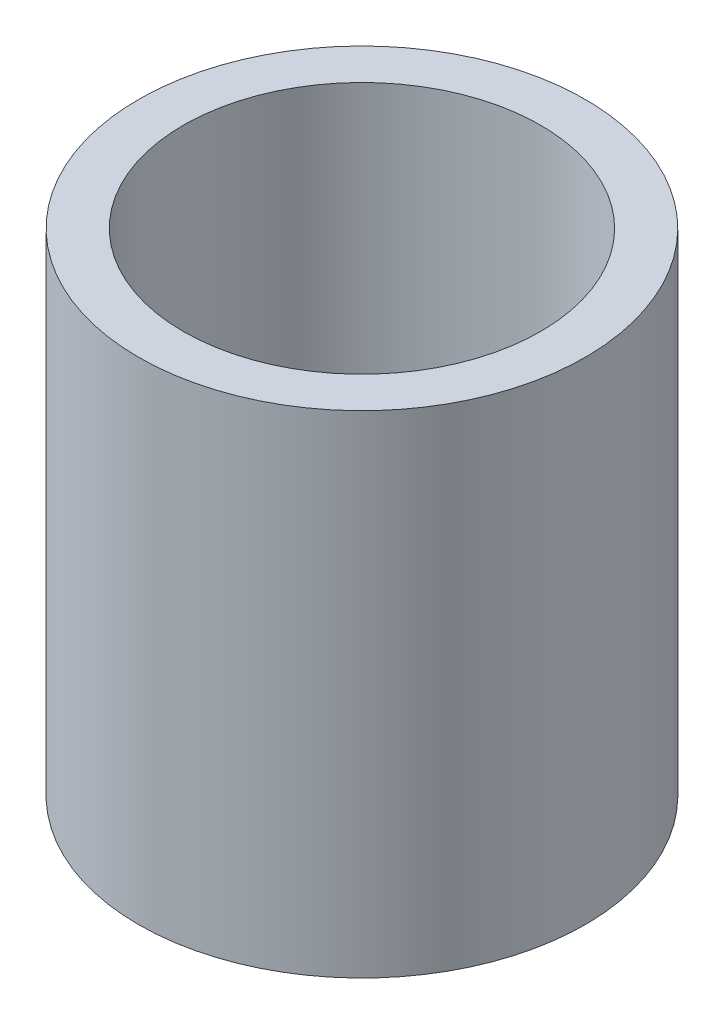
SolidWorks part; units mm, degrees
ref_plane "Front Plane" through (0, 0, 0) normal (0, 0, 1) x (1, 0, 0)
ref_plane "Top Plane" through (0, 0, 0) normal (0, 1, 0) x (1, 0, 0)
ref_plane "Right Plane" through (0, 0, 0) normal (1, 0, 0) x (0, 0, -1)
sketch "Sketch1" plane through (0, 0, 0) normal (0, 1, 0) x (1, 0, 0)
  line L0 (-1.0896, 0) -> (1.083, 0) construction
  line L1 (-0.0033, 0.9576) -> (-0.0033, -0.8453) construction
  circle A0 centre (0, 0) radius 0.625
  circle A1 centre (0, 0) radius 0.5
  dimension "D1" = 1.25
  dimension "D2" = 1
extrude "Boss-Extrude1" add sketch "Sketch1" along normal blind 1.375
